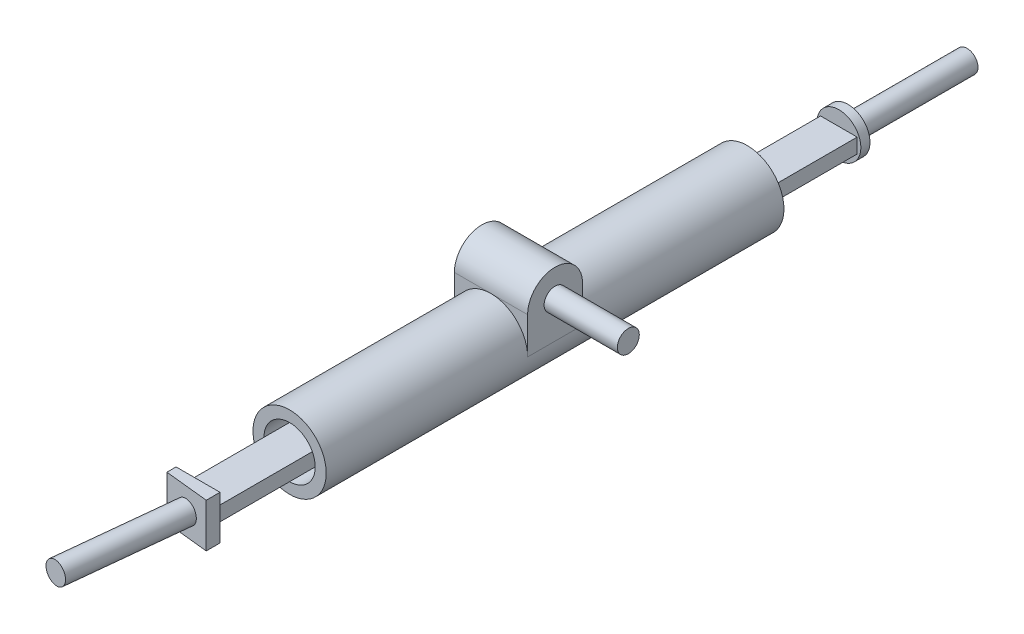
SolidWorks part; units mm, degrees
ref_plane "Płaszczyzna przednia" through (0, 0, 0) normal (0, 0, 1) x (1, 0, 0)
ref_plane "Płaszczyzna górna" through (0, 0, 0) normal (0, 1, 0) x (1, 0, 0)
ref_plane "Płaszczyzna prawa" through (0, 0, 0) normal (1, 0, 0) x (0, 0, -1)
sketch "Szkic1" plane through (0, 0, 0) normal (0, 0, 1) x (1, 0, 0)
  line L1 (-10, -4) -> (10, -4)
  line L2 (-10, -4) -> (-10, 4)
  line L3 (-10, 4) -> (10, 4)
  line L4 (10, -4) -> (10, 4)
  line L5 (-10, -4) -> (10, 4) construction
  line L6 (-10, 4) -> (10, -4) construction
  point P0 (0, 0)
  dimension "D1" = 20
  dimension "D2" = 8
extrude "Dodanie-wyciągnięcie1" add sketch "Szkic1" along normal blind 350
sketch "Szkic2" plane through (0, 0, 350) normal (0, 0, 1) x (1, 0, 0)
  circle A0 centre (0, 0) radius 12
extrude "Dodanie-wyciągnięcie2" add sketch "Szkic2" along normal blind 5
sketch "Szkic3" plane through (0, 0, 0) normal (0, 0, -1) x (-1, 0, 0)
  circle A0 centre (0, 0) radius 12
extrude "Dodanie-wyciągnięcie3" add sketch "Szkic3" along normal blind 5
sketch "Szkic5" plane through (0, 4, 0) normal (0, 1, 0) x (1, 0, 0)
  line L0 (-12, -350) -> (12, -350)
  line L1 (12, -350) -> (-12, -350) construction
  line L2 (12, -350) -> (12, -357.5225)
  line L3 (-12, -350) -> (-12, -355)
  line L4 (-12, -355) -> (12, -357.5225)
  dimension "D1" = 6
  dimension "D2" = 24
extrude "Dodanie-wyciągnięcie4" add sketch "Szkic5" along normal blind 8 and the other way blind 16
sketch "Szkic6" plane through (-37.0354, 0, 352.3687) normal (-0.1045, 0, 0.9945) x (0.9945, 0, 0.1045)
  circle A0 centre (37.2394, 0) radius 6
extrude "Dodanie-wyciągnięcie5" add sketch "Szkic6" along normal blind 65
sketch "Szkic7" plane through (0, 0, -5) normal (0, 0, -1) x (-1, 0, 0)
  circle A0 centre (0, 0) radius 6
extrude "Dodanie-wyciągnięcie6" add sketch "Szkic7" along normal blind 65
sketch "Szkic8" plane through (0, 0, 350) normal (0, 0, -1) x (-1, 0, 0)
  circle A0 centre (0, 0) radius 14
  circle A1 centre (0, 0) radius 20
extrude "Dodanie-wyciągnięcie7" add sketch "Szkic8" along normal blind 300
sketch "Szkic13" plane through (0, 0, 350) normal (0, 0, 1) x (1, 0, 0)
  circle A0 centre (0, 0) radius 14
  circle A1 centre (0, 0) radius 20
extrude "Wytnij-wyciągnięcie1" cut sketch "Szkic13" against normal blind 50
sketch "Szkic14" plane through (0, 0, 0) normal (1, 0, 0) x (0, 0, -1)
  line L0 (0, 0) -> (-175, 0)
  line L1 (-175, 0) -> (-175, 35)
  line L2 (-175, 35) -> (-160, 35)
  line L3 (-160, 35) -> (-160, 0)
  line L4 (-160, 0) -> (-190, 0)
  line L5 (-190, 0) -> (-190, 35)
  line L6 (-190, 35) -> (-175, 35)
extrude "Dodanie-wyciągnięcie9" add sketch "Szkic14" along normal blind 20 and the other way blind 20 contours L2 L3 L4 L5 L6
sketch "Szkic15" plane through (20, 0, 0) normal (1, 0, 0) x (0, 0, -1)
  line L1 (-190, 20) -> (-194.5817, 20)
  line L2 (-194.5817, 20) -> (-195.363, 44.0375)
  line L3 (-195.363, 44.0375) -> (-145.6755, 44.0375)
  line L4 (-145.6755, 44.0375) -> (-145.6755, 20)
  line L5 (-145.6755, 20) -> (-160, 20)
  circle A1 centre (-175, 20) radius 15
  line M1 (-160, 35) -> (-190, 35)
  line M2 (-190, 35) -> (-190, 0)
  line M4 (-160, 0) -> (-160, 35)
extrude "Wytnij-wyciągnięcie2" cut sketch "Szkic15" against normal blind 40 contours A1 M1 M2 | A1 M4 M1
sketch "Szkic16" plane through (20, 0, 0) normal (1, 0, 0) x (0, 0, -1)
  circle A0 centre (-175, 20) radius 6
extrude "Dodanie-wyciągnięcie10" add sketch "Szkic16" along normal blind 40
